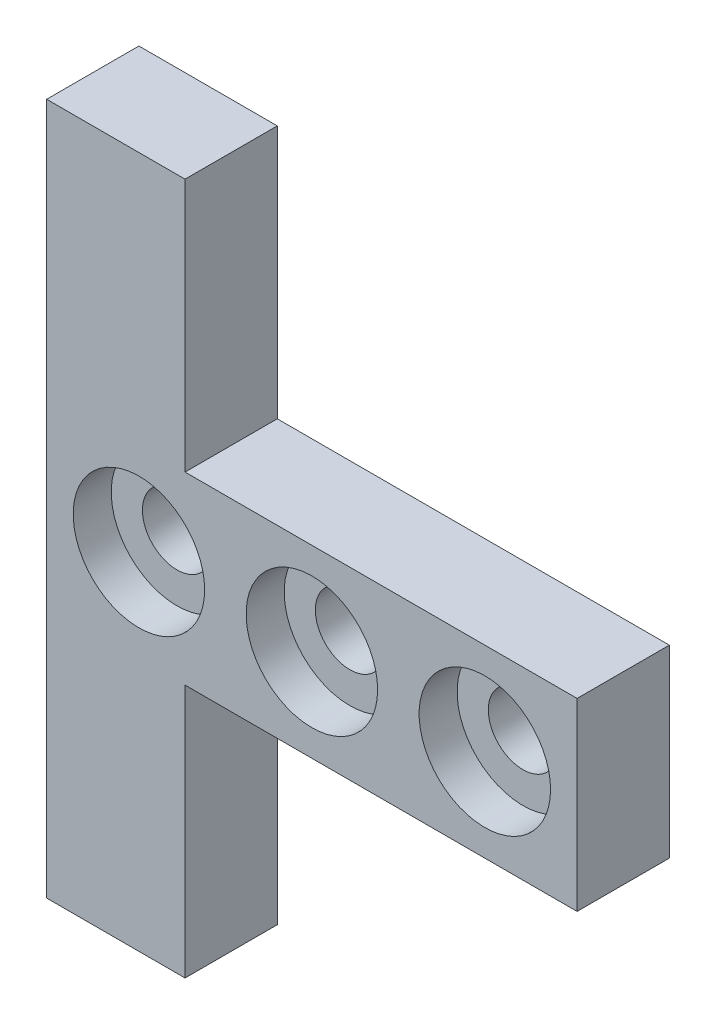
SolidWorks part; units mm, degrees
ref_plane "Alzado" through (0, 0, 0) normal (0, 0, 1) x (1, 0, 0)
ref_plane "Planta" through (0, 0, 0) normal (0, 1, 0) x (1, 0, 0)
ref_plane "Vista lateral" through (0, 0, 0) normal (1, 0, 0) x (0, 0, -1)
sketch "Croquis2" plane through (0, 0, 0) normal (0, 0, 1) x (1, 0, 0)
  line L1 (43.9972, -189.7054) -> (43.9972, -185.7054) construction
  line L2 (38.4972, -99.7054) -> (38.4972, -279.7054) construction
  line L4 (55.9972, -189.7054) -> (55.9972, -185.7054) construction
  line L7 (46.4972, -264.7054) -> (46.4972, -114.7054) construction
  line L21 (38.4972, -264.7054) -> (38.4972, -114.7054) construction
  line L22 (38.4972, -99.7054) -> (38.4972, -279.7054) construction
  line L23 (38.4972, -99.7054) -> (38.4972, -114.7054) construction
  line L24 (38.4972, -114.7054) -> (-55.1416, -114.7054) construction
  line L25 (-55.1416, -264.7054) -> (38.4972, -264.7054) construction
  line L26 (46.4972, -204.7054) -> (46.4972, -193.7054)
  line L27 (46.4972, -185.7054) -> (46.4972, -174.7054)
  line L28 (38.4972, -114.7054) -> (42.4972, -114.7054) construction
  line L29 (57.4972, -114.7054) -> (73.4972, -114.7054) construction
  line L30 (38.4972, -189.7054) -> (222.4972, -189.7054) construction
  line L31 (222.4972, -279.7054) -> (222.4972, -99.7054) construction
  line L35 (42.4972, -204.7054) -> (42.4972, -174.7054) construction
  line L36 (46.4972, -189.7054) -> (38.4972, -189.7054)
  line L37 (46.4972, -189.7054) -> (46.4972, -174.7054) construction
  line L38 (46.4972, -174.7054) -> (38.4972, -174.7054)
  line L39 (38.4972, -189.7054) -> (38.4972, -174.7054)
  line L40 (46.4972, -189.7054) -> (38.4972, -189.7054)
  line L41 (46.4972, -189.7054) -> (46.4972, -204.7054) construction
  line L42 (46.4972, -204.7054) -> (38.4972, -204.7054)
  line L43 (38.4972, -189.7054) -> (38.4972, -204.7054)
  line L44 (46.4972, -193.7054) -> (61.4972, -193.7054)
  line L45 (46.4972, -193.7054) -> (46.4972, -185.7054)
  line L46 (46.4972, -185.7054) -> (61.4972, -185.7054)
  line L47 (61.4972, -193.7054) -> (61.4972, -185.7054)
  line L48 (46.4972, -193.7054) -> (38.4972, -193.7054) construction
  line L49 (46.4972, -185.7054) -> (38.4972, -185.7054) construction
  line L50 (38.4972, -204.7054) -> (46.4972, -193.7054) construction
  line L51 (38.4972, -193.7054) -> (46.4972, -204.7054) construction
  line L52 (46.4972, -185.7054) -> (38.4972, -174.7054) construction
  line L53 (46.4972, -174.7054) -> (38.4972, -185.7054) construction
  circle A0 centre (57.4972, -189.7054) radius 1.5
  circle A6 centre (42.4972, -189.7054) radius 1.5
  circle A7 centre (49.9972, -189.7054) radius 1.5
  dimension "D8" = 3
  dimension "D10" = 3
  dimension "D11" = 3
  dimension "D1" = 8
  dimension "D2" = 15
  dimension "D3" = 15
  dimension "D4" = 8
  dimension "D5" = 15
  dimension "D9" = 4
  dimension "D12" = 6
extrude "Saliente-Extruir1" add sketch "Croquis2" along normal blind 4
sketch "Croquis3" plane through (0, 0, 4) normal (0, 0, 1) x (1, 0, 0)
  circle A2 centre (42.4972, -189.7054) radius 2.85
  circle A4 centre (49.9972, -189.7054) radius 2.85
  circle A5 centre (57.4972, -189.7054) radius 2.85
  dimension "D2" = 5.7
extrude "Cortar-Extruir1" cut sketch "Croquis3" against normal blind 1.65
sketch "Croquis4" plane through (46.4972, 0, 0) normal (1, 0, 0) x (0, 0, -1)
  line L1 (-4, -204.7054) -> (0, -204.7054)
  line L2 (-4, -204.7054) -> (-4, -193.7054)
  line L3 (-4, -193.7054) -> (0, -193.7054)
  line L4 (0, -204.7054) -> (0, -193.7054)
  line L5 (-4, -204.7054) -> (0, -193.7054) construction
  line L6 (-4, -193.7054) -> (0, -204.7054) construction
  line L7 (-4, -185.7054) -> (0, -185.7054)
  line L8 (-4, -185.7054) -> (-4, -174.7054)
  line L9 (-4, -174.7054) -> (0, -174.7054)
  line L10 (0, -185.7054) -> (0, -174.7054)
  line L11 (-4, -185.7054) -> (0, -174.7054) construction
  line L12 (-4, -174.7054) -> (0, -185.7054) construction
  point P4 (-2, -199.2054)
  point P11 (-2, -180.2054)
extrude "Cortar-Extruir2" cut sketch "Croquis4" against normal blind 2
